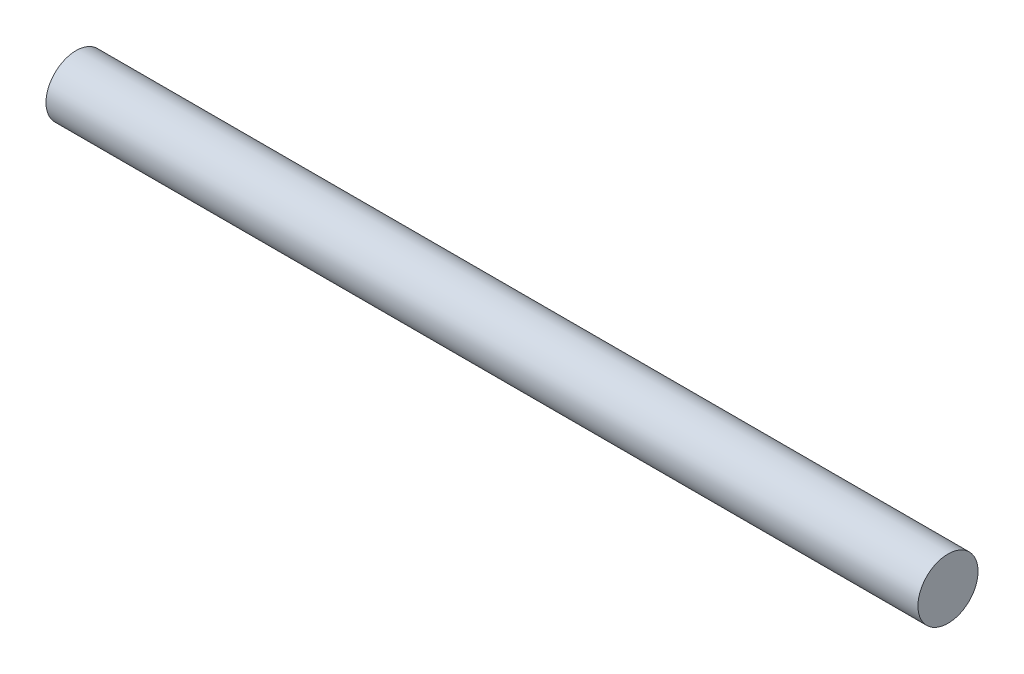
SolidWorks part; units mm, degrees
material "AISI 1020"
ref_plane "Спереди" through (0, 0, 0) normal (0, 0, 1) x (1, 0, 0)
ref_plane "Сверху" through (0, 0, 0) normal (0, 1, 0) x (1, 0, 0)
ref_plane "Справа" through (0, 0, 0) normal (1, 0, 0) x (0, 0, -1)
sketch "Эскиз1" plane through (0, 0, 0) normal (1, 0, 0) x (0, 0, -1)
  circle A0 centre (0, 0) radius 1
  dimension "D1" = 2
extrude "Бобышка-Вытянуть1" add sketch "Эскиз1" along normal mid plane 29
